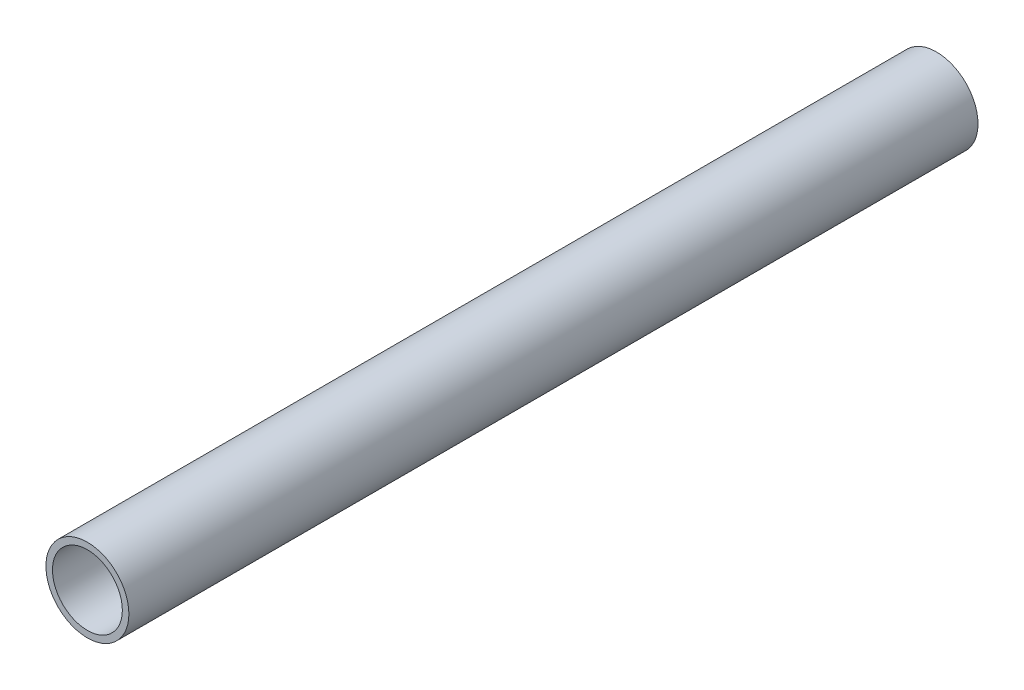
SolidWorks part; units mm, degrees
material "AISI 1020"
ref_plane "Plano frontal" through (0, 0, 0) normal (0, 0, 1) x (1, 0, 0)
ref_plane "Plano superior" through (0, 0, 0) normal (0, 1, 0) x (1, 0, 0)
ref_plane "Plano direito" through (0, 0, 0) normal (1, 0, 0) x (0, 0, -1)
sketch "Esboço2" plane through (0, 0, 0) normal (0, 0, 1) x (1, 0, 0)
  circle A0 centre (0, 0) radius 12.7
  circle A1 centre (0, 0) radius 10.7
  dimension "D1" = 25.4
  dimension "D2" = 2
extrude "Ressalto-extrusão1" add sketch "Esboço2" along normal blind 260
